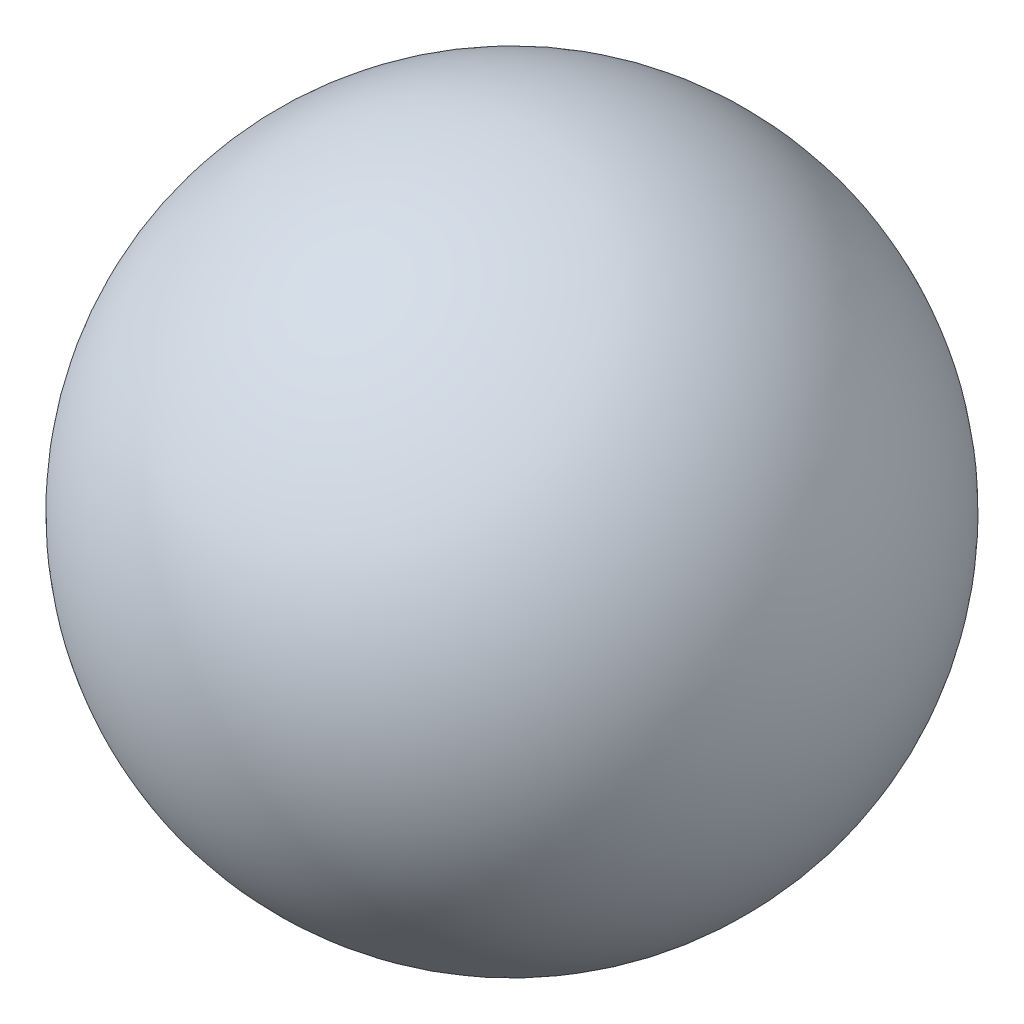
SolidWorks part; units mm, degrees
ref_plane "Front" through (0, 0, 0) normal (0, 0, 1) x (1, 0, 0)
ref_plane "Top" through (0, 0, 0) normal (0, 1, 0) x (1, 0, 0)
ref_plane "Right" through (0, 0, 0) normal (1, 0, 0) x (0, 0, -1)
sketch "Sketch1" plane through (0, 0, 0) normal (0, 1, 0) x (1, 0, 0)
  line L0 (0, 0) -> (0, 21.41) construction
  line L1 (0, 0) -> (0, -21.41) construction
  line L2 (0, 21.41) -> (0, -21.41)
  arc A0 (0, 21.41) -> (0, -21.41) centre (0, 0) ccw
  dimension "D1" = 42.82
revolve "Revolve5" add sketch "Sketch1" angle 360 about L2
